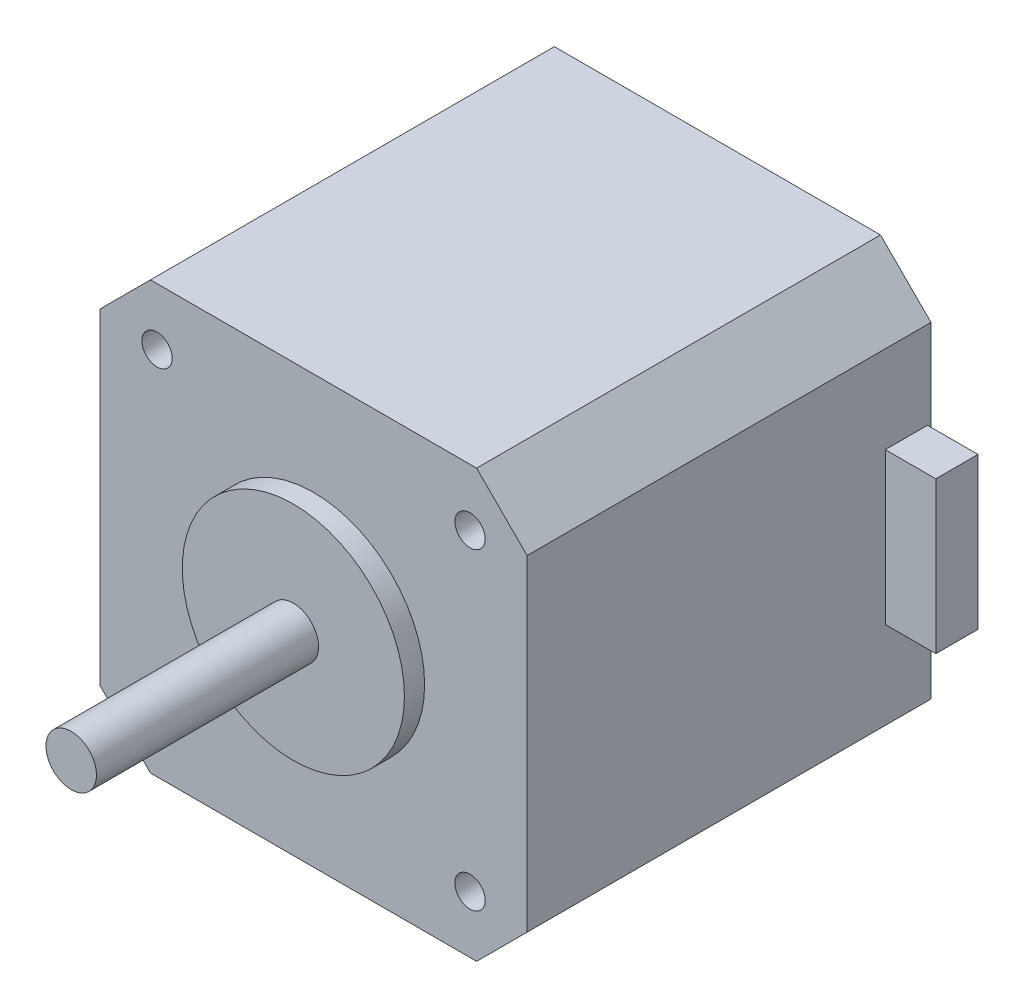
SolidWorks part; units mm, degrees
ref_plane "Plano frontal" through (0, 0, 0) normal (0, 0, 1) x (1, 0, 0)
ref_plane "Plano superior" through (0, 0, 0) normal (0, 1, 0) x (1, 0, 0)
ref_plane "Plano direito" through (0, 0, 0) normal (1, 0, 0) x (0, 0, -1)
sketch "Esboço1" plane through (0, 0, 0) normal (0, 0, 1) x (1, 0, 0)
  line L0 (-21.15, 16.15) -> (-16.15, 21.15)
  line L1 (-16.15, 21.15) -> (16.15, 21.15)
  line L2 (-21.15, 16.15) -> (-21.15, -16.15)
  line L3 (-16.15, -21.15) -> (16.15, -21.15)
  line L4 (21.15, 16.15) -> (21.15, -16.15)
  line L5 (-21.15, 21.15) -> (21.15, -21.15) construction
  line L6 (-21.15, -21.15) -> (21.15, 21.15) construction
  line L7 (-15.5, 15.5) -> (15.5, 15.5) construction
  line L8 (-15.5, 15.5) -> (-15.5, -15.5) construction
  line L9 (-15.5, -15.5) -> (15.5, -15.5) construction
  line L10 (15.5, 15.5) -> (15.5, -15.5) construction
  line L11 (-21.15, -16.15) -> (-16.15, -21.15)
  line L12 (16.15, 21.15) -> (21.15, 16.15)
  line L13 (16.15, -21.15) -> (21.15, -16.15)
  point P4 (0, 0)
  point P13 (15.5, 0)
  dimension "D4" = 5
  dimension "D1" = 42.3
  dimension "D2" = 42.3
  dimension "D3" = 31
  dimension "D5" = 5
  dimension "D6" = 5
  dimension "D7" = 5
  dimension "D8" = 5
  dimension "D9" = 5
  dimension "D10" = 5
  dimension "D11" = 5
extrude "Ressalto-extrusão1" add sketch "Esboço1" along normal blind 40
sketch "Esboço2" plane through (0, 0, 40) normal (0, 0, 1) x (1, 0, 0)
  circle A0 centre (0, 0) radius 11
  dimension "D1" = 22
extrude "Ressalto-extrusão2" add sketch "Esboço2" along normal blind 2
sketch "Esboço3" plane through (0, 0, 42) normal (0, 0, 1) x (1, 0, 0)
  circle A0 centre (0, 0) radius 2.5
  dimension "D1" = 5
extrude "Ressalto-extrusão3" add sketch "Esboço3" along normal blind 22
sketch "Esboço4" plane through (0, 0, 40) normal (0, 0, 1) x (1, 0, 0)
  line L1 (-15.5, 15.5) -> (15.5, 15.5) construction
  line L2 (-15.5, 15.5) -> (-15.5, -15.5) construction
  line L3 (-15.5, -15.5) -> (15.5, -15.5) construction
  line L4 (15.5, 15.5) -> (15.5, -15.5) construction
  line L5 (-15.5, 15.5) -> (15.5, -15.5) construction
  line L6 (-15.5, -15.5) -> (15.5, 15.5) construction
  circle A0 centre (15.5, -15.5) radius 1.5
  circle A1 centre (15.5, 15.5) radius 1.5
  circle A2 centre (-15.5, -15.5) radius 1.5
  circle A3 centre (-15.5, 15.5) radius 1.5
  point P4 (0, 0)
  dimension "D2" = 3
  dimension "D1" = 31
extrude "Corte-extrusão1" cut sketch "Esboço4" against normal blind 15
sketch "Esboço5" plane through (21.15, 0, 0) normal (1, 0, 0) x (0, 0, -1)
  line L1 (-4.5263, -7.5) -> (-0.3467, -7.5)
  line L2 (-4.5263, -7.5) -> (-4.5263, 7.5)
  line L3 (-4.5263, 7.5) -> (-0.3467, 7.5)
  line L4 (-0.3467, -7.5) -> (-0.3467, 7.5)
  line L5 (-4.5263, -7.5) -> (-0.3467, 7.5) construction
  line L6 (-4.5263, 7.5) -> (-0.3467, -7.5) construction
  point P4 (-2.4365, 0)
  dimension "D1" = 15
extrude "Ressalto-extrusão4" add sketch "Esboço5" along normal blind 5
